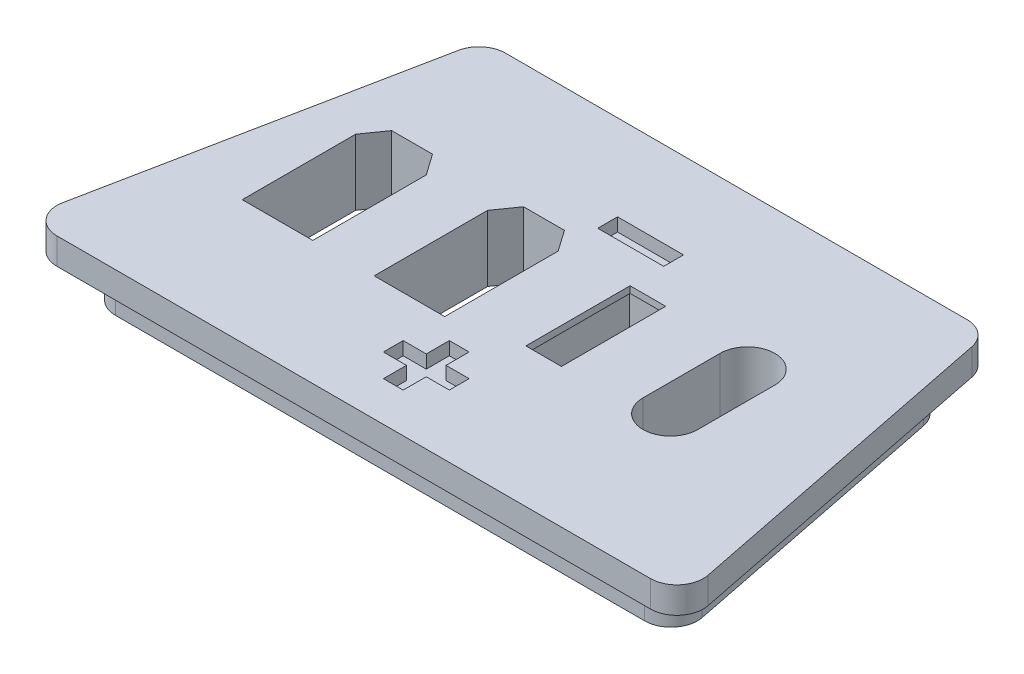
SolidWorks part; units mm, degrees
ref_plane "Front Plane" through (0, 0, 0) normal (0, 0, 1) x (1, 0, 0)
ref_plane "Top Plane" through (0, 0, 0) normal (0, 1, 0) x (1, 0, 0)
ref_plane "Right Plane" through (0, 0, 0) normal (1, 0, 0) x (0, 0, -1)
sketch "Sketch1" plane through (0, 0, 0) normal (0, 1, 0) x (1, 0, 0)
  line L0 (-17.5, 12.5) -> (17.5, 12.5)
  line L1 (17.5, 12.5) -> (22.5, -12.5)
  line L2 (22.5, -12.5) -> (-22.5, -12.5)
  line L3 (-22.5, -12.5) -> (-17.5, 12.5)
  line L4 (0, -44.7868) -> (0, 44.7868) construction
  line L5 (-44.2539, 0) -> (44.2539, 0) construction
  dimension "D1" = 35
  dimension "D2" = 45
  dimension "D3" = 25
  dimension "D4" = 17.5
  dimension "D5" = 12.5
extrude "Boss-Extrude1" add sketch "Sketch1" along normal blind 3
sketch "Sketch2" plane through (0, 3, 0) normal (0, 1, 0) x (1, 0, 0)
  line L0 (-19.1396, 14.5) -> (19.1396, 14.5)
  line L1 (19.1396, 14.5) -> (24.9396, -14.5)
  line L2 (24.9396, -14.5) -> (-24.9396, -14.5)
  line L3 (-24.9396, -14.5) -> (-19.1396, 14.5)
  line L4 (17.5, 12.5) -> (-17.5, 12.5) construction
  line L5 (-22.5, -12.5) -> (22.5, -12.5) construction
  line L7 (22.5, -12.5) -> (17.5, 12.5) construction
  line L8 (-17.5, 12.5) -> (-22.5, -12.5) construction
  dimension "D1" = 2
  dimension "D2" = 2
  dimension "D3" = 2
  dimension "D4" = 2
extrude "Boss-Extrude2" add sketch "Sketch2" along normal blind 2
fillet "Fillet1" radius 2 8 edges at (-17.5, 1.5, -12.5) (17.5, 1.5, -12.5) (22.5, 1.5, 12.5) (-22.5, 1.5, 12.5) (-24.9396, 4, 14.5) (24.9396, 4, 14.5) (19.1396, 4, -14.5) (-19.1396, 4, -14.5)
sketch "Sketch3" plane through (0, 5, 0) normal (0, 1, 0) x (1, 0, 0)
  line L0 (-7.85, -5.1) -> (-2.5, -5.1)
  line L1 (-2.5, -5.1) -> (-2.5, 3.5)
  line L2 (-2.5, 3.5) -> (-3.625, 5.1)
  line L3 (-3.625, 5.1) -> (-6.725, 5.1)
  line L4 (-6.725, 5.1) -> (-7.85, 3.5)
  line L5 (-7.85, 3.5) -> (-7.85, -5.1)
  line L7 (-44.2539, 0) -> (44.2539, 0) construction
  line L8 (0, -44.7868) -> (0, 44.7868) construction
  dimension "D1" = 5.35
  dimension "D2" = 10.2
  dimension "D3" = 3.1
  dimension "D4" = 1.6
  dimension "D5" = 5.1
  dimension "D6" = 2.5
extrude "Cut-Extrude1" cut sketch "Sketch3" against normal up to surface (5 mm away) up to face at (0, 0, -0.1677)
pattern_linear "LPattern1" count 2 spacing 10 along (-1, 0, 0) of "Cut-Extrude1"
sketch "Sketch5" plane through (0, 0, 0) normal (0, -1, 0) x (1, 0, 0)
  line L0 (44.2539, 0) -> (-44.2539, 0) construction
  line L1 (2.5, 3.95) -> (5.2, 3.95)
  line L2 (2.5, 3.95) -> (2.5, -3.95)
  line L3 (2.5, -3.95) -> (5.2, -3.95)
  line L4 (5.2, 3.95) -> (5.2, -3.95)
  line L5 (0, -44.7868) -> (0, 44.7868) construction
  dimension "D1" = 7.9
  dimension "D2" = 3.95
  dimension "D3" = 2.7
  dimension "D4" = 2.5
extrude "Cut-Extrude2" cut sketch "Sketch5" against normal up to surface (5 mm away) up to face at (-15.175, 5, -1.1667)
sketch "Sketch6" plane through (0, 0, 0) normal (0, -1, 0) x (1, 0, 0)
  line L0 (44.2539, 0) -> (-44.2539, 0) construction
  line L1 (2.35, 4.05) -> (5.35, 4.05)
  line L2 (2.35, 4.05) -> (2.35, -4.05)
  line L3 (2.35, -4.05) -> (5.35, -4.05)
  line L4 (5.35, 4.05) -> (5.35, -4.05)
  line L5 (5.2, -3.95) -> (5.2, 3.95) construction
  dimension "D1" = 8.1
  dimension "D2" = 4.05
  dimension "D3" = 3
  dimension "D4" = 0.15
extrude "Cut-Extrude3" cut sketch "Sketch6" against normal blind 4.5
sketch "Sketch7" plane through (0, 0, 0) normal (0, -1, 0) x (1, 0, 0)
  line L0 (12.43, 2.92) -> (12.43, -2.92) construction
  line L1 (14.51, 2.92) -> (14.51, -2.92)
  line L2 (10.35, 2.92) -> (10.35, -2.92)
  line L3 (5.35, -4.05) -> (5.35, 4.05) construction
  line L4 (44.2539, 0) -> (-44.2539, 0) construction
  arc A0 (14.51, 2.92) -> (10.35, 2.92) centre (12.43, 2.92) ccw
  arc A1 (10.35, -2.92) -> (14.51, -2.92) centre (12.43, -2.92) ccw
  point P2 (12.43, 0)
  point P7 (12.43, 5)
  point P8 (12.43, -5)
  dimension "D1" = 4.16
  dimension "D2" = 10
  dimension "D3" = 5
  dimension "D4" = 5
extrude "USB-C Hole" cut sketch "Sketch7" against normal up to surface (5 mm away) up to face at (3.85, 5, 0)
sketch "Sketch8" plane through (0, 5, 0) normal (0, 1, 0) x (1, 0, 0)
  line L0 (0, -44.7868) -> (0, 44.7868) construction
  line L1 (-0.75, -6.5) -> (0.75, -6.5)
  line L2 (-0.75, -6.5) -> (-0.75, -11.5)
  line L3 (-0.75, -11.5) -> (0.75, -11.5)
  line L4 (0.75, -6.5) -> (0.75, -11.5)
  line L5 (-2.5, -8.25) -> (2.5, -8.25)
  line L6 (-2.5, -8.25) -> (-2.5, -9.75)
  line L7 (-2.5, -9.75) -> (2.5, -9.75)
  line L8 (2.5, -8.25) -> (2.5, -9.75)
  line L9 (-2.5, 8) -> (2.5, 8)
  line L10 (-2.5, 8) -> (-2.5, 6.5)
  line L11 (-2.5, 6.5) -> (2.5, 6.5)
  line L12 (2.5, 8) -> (2.5, 6.5)
  line L13 (-44.2539, 0) -> (44.2539, 0) construction
  dimension "D1" = 1.5
  dimension "D2" = 5
  dimension "D3" = 2.5
  dimension "D4" = 1.5
  dimension "D5" = 5
  dimension "D6" = 1.75
  dimension "D7" = 1.75
  dimension "D8" = 6.5
  dimension "D9" = 1.5
  dimension "D10" = 5
  dimension "D11" = 6.5
  dimension "D12" = 2.5
extrude "PosNegSigns" cut sketch "Sketch8" against normal blind 1 contours L6 L7 L2 L5 | L7 L2 L3 L4 | L2 L7 L4 L5 | L8 L5 L4 L7 | L2 L5 L4 L1 | L12 L9 L10 L11
